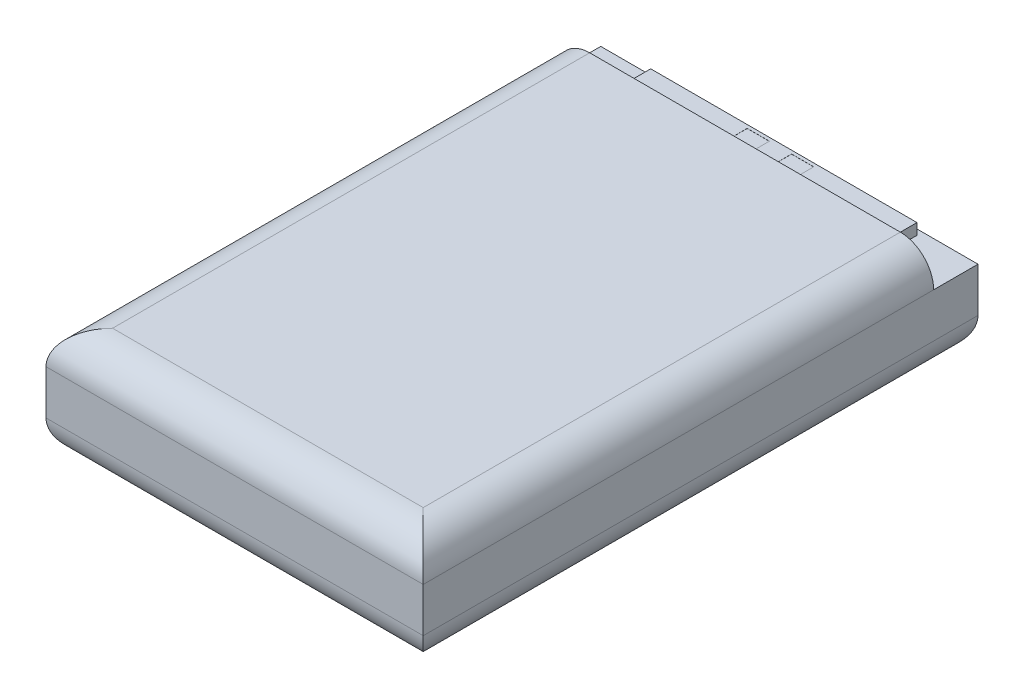
SolidWorks part; units mm, degrees
ref_plane "Спереди" through (0, 0, 0) normal (0, 0, 1) x (1, 0, 0)
ref_plane "Сверху" through (0, 0, 0) normal (0, 1, 0) x (1, 0, 0)
ref_plane "Справа" through (0, 0, 0) normal (1, 0, 0) x (0, 0, -1)
sketch "Эскиз1" plane through (0, 0, 0) normal (0, 1, 0) x (1, 0, 0)
  line L1 (17, -25) -> (-17, -25)
  line L2 (17, -25) -> (17, 25)
  line L3 (17, 25) -> (-17, 25)
  line L4 (-17, -25) -> (-17, 25)
  line L5 (17, -25) -> (-17, 25) construction
  line L6 (17, 25) -> (-17, -25) construction
  point P0 (0, 0)
  dimension "D1" = 34
  dimension "D2" = 50
extrude "Бобышка-Вытянуть1" add sketch "Эскиз1" along normal blind 10
fillet "Скругление1" radius 3 7 edges at (0, 0, -25) (0, 0, 25) (0, 10, 25) (17, 0, 0) (17, 10, 0) (-17, 0, 0) (-17, 10, 0)
sketch "Эскиз2" plane through (0, 10, 0) normal (0, 1, 0) x (1, 0, 0)
  line L0 (14, 25) -> (-14, 25) construction
  line L1 (-18, 26) -> (18, 26)
  line L2 (-18, 26) -> (-18, 21)
  line L3 (-18, 21) -> (18, 21)
  line L4 (18, 26) -> (18, 21)
  line L5 (17, 25) -> (17, -25) construction
  line L6 (-17, -25) -> (-17, 25) construction
  dimension "D1" = 4
  dimension "D2" = 1
  dimension "D3" = 1
  dimension "D4" = 1
extrude "Вырез-Вытянуть1" cut sketch "Эскиз2" against normal blind 3
sketch "Эскиз3" plane through (0, 7, 0) normal (0, 1, 0) x (1, 0, 0)
  line L0 (-17, 25) -> (-17, 21) construction
  line L1 (-12, 24.5) -> (12, 24.5)
  line L2 (-12, 24.5) -> (-12, 21)
  line L3 (-12, 21) -> (12, 21)
  line L4 (12, 24.5) -> (12, 21)
  line L5 (17, 25) -> (17, 21) construction
  line L6 (-14, 21) -> (14, 21) construction
  line L7 (17, 25) -> (-17, 25) construction
  dimension "D1" = 5
  dimension "D2" = 5
  dimension "D3" = 0
  dimension "D4" = 0.5
extrude "Бобышка-Вытянуть2" add sketch "Эскиз3" along normal blind 1
sketch "Эскиз4" plane through (0, 8, 0) normal (0, 1, 0) x (1, 0, 0)
  line L0 (-14, 21) -> (14, 21) construction
  line L1 (-3, 24.2) -> (-1, 24.2)
  line L2 (-3, 24.2) -> (-3, 21.3)
  line L3 (-3, 21.3) -> (-1, 21.3)
  line L4 (-1, 24.2) -> (-1, 21.3)
  line L5 (1, 24.2) -> (3, 24.2)
  line L6 (1, 24.2) -> (1, 21.3)
  line L7 (1, 21.3) -> (3, 21.3)
  line L8 (3, 24.2) -> (3, 21.3)
  line L9 (12, 24.5) -> (-12, 24.5) construction
  line L10 (12, 24.5) -> (-12, 24.5) construction
  dimension "D1" = 1
  dimension "D2" = 1
  dimension "D3" = 0.3
  dimension "D4" = 0.3
  dimension "D5" = 2
  dimension "D6" = 0.3
  dimension "D7" = 0.3
  dimension "D8" = 2
extrude "Вырез-Вытянуть2" cut sketch "Эскиз4" against normal blind 0.01
